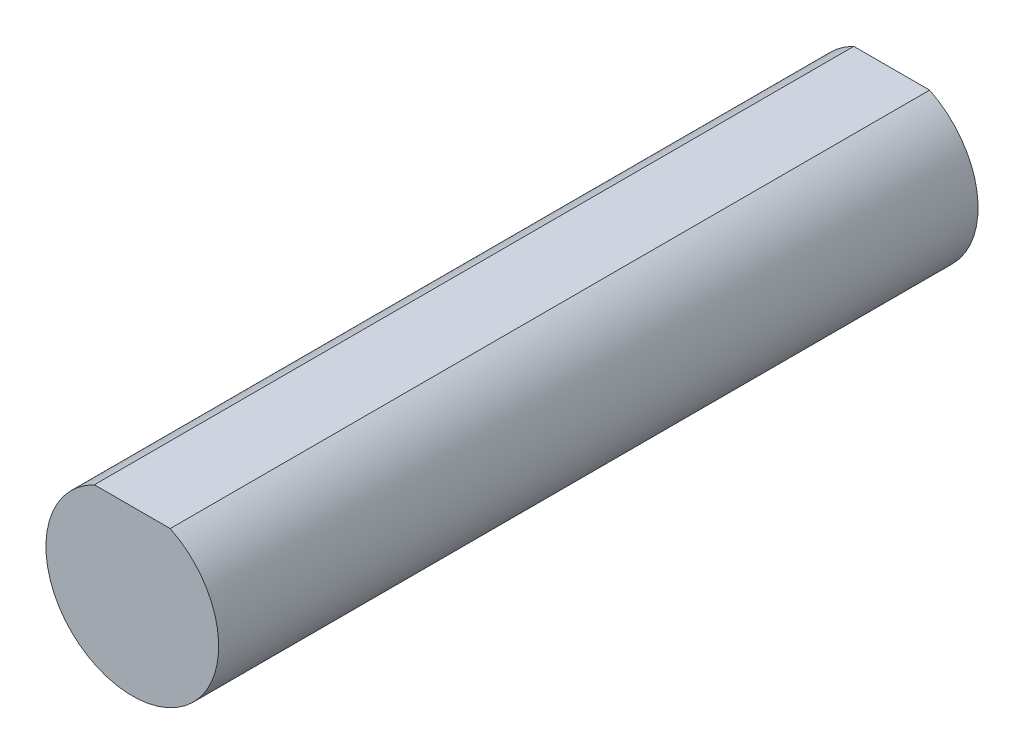
SolidWorks part; units mm, degrees
ref_plane "Front Plane" through (0, 0, 0) normal (0, 0, 1) x (1, 0, 0)
ref_plane "Top Plane" through (0, 0, 0) normal (0, 1, 0) x (1, 0, 0)
ref_plane "Right Plane" through (0, 0, 0) normal (1, 0, 0) x (0, 0, -1)
sketch "Sketch1" plane through (0, 0, 0) normal (0, 0, 1) x (1, 0, 0)
  circle A0 centre (0, 0) radius 2.5019
  dimension "D1" = 5.0038
extrude "Boss-Extrude1" add sketch "Sketch1" along normal blind 21.9964
sketch "Sketch3" plane through (0, 0, 21.9964) normal (0, 0, 1) x (1, 0, 0)
  line L0 (-1.0984, 2.2479) -> (1.0984, 2.2479)
  circle A0 centre (0, 0) radius 2.5019 construction
  arc A1 (-1.0984, 2.2479) -> (1.0984, 2.2479) centre (0, 0) cw
  dimension "D1" = 2.2479
extrude "Cut-Extrude1" cut sketch "Sketch3" against normal blind 21.9964
